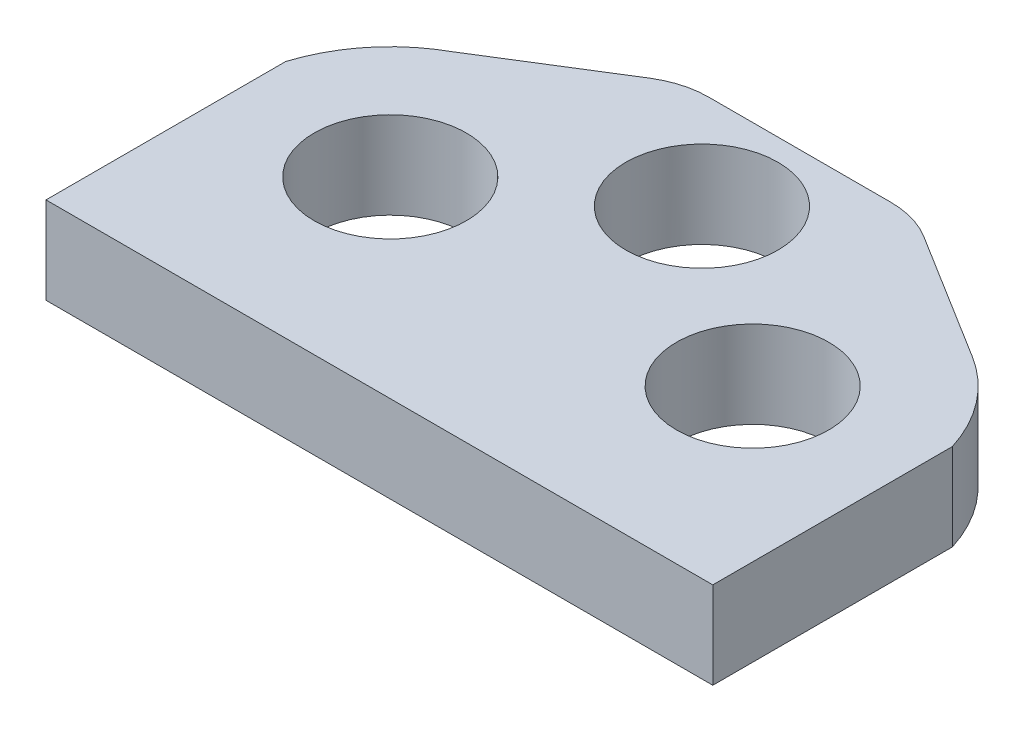
SolidWorks part; units mm, degrees
material "Beech"
ref_plane "Front Plane" through (0, 0, 0) normal (0, 0, 1) x (1, 0, 0)
ref_plane "Top Plane" through (0, 0, 0) normal (0, 1, 0) x (1, 0, 0)
ref_plane "Right Plane" through (0, 0, 0) normal (1, 0, 0) x (0, 0, -1)
sketch "Sketch1" plane through (0, 0, 0) normal (0, 1, 0) x (1, 0, 0)
  line L1 (-46, 28) -> (46, 28)
  line L2 (-46, 28) -> (-46, -28)
  line L3 (-46, -28) -> (46, -28)
  line L4 (46, 28) -> (46, -28)
  line L5 (-46, 28) -> (46, -28) construction
  line L6 (-46, -28) -> (46, 28) construction
  point P0 (0, 0)
  dimension "D1" = 56
  dimension "D2" = 92
extrude "Boss-Extrude1" add sketch "Sketch1" along normal blind 12
sketch "Sketch8" plane through (0, 12, 0) normal (0, 1, 0) x (1, 0, 0)
  line L1 (-46, 28) -> (46, 28)
  line L2 (-46, 28) -> (-46, 30)
  line L3 (-46, 30) -> (46, 30)
  line L4 (46, 28) -> (46, 30)
  dimension "D1" = 2
extrude "Boss-Extrude3" add sketch "Sketch8" against normal blind 12
sketch "Sketch2" plane through (0, 12, 0) normal (0, 1, 0) x (1, 0, 0)
  line L0 (-55.7629, -1.5) -> (57.1831, -1.5) construction
  line L1 (-46, -28) -> (46, -28) construction
  circle A0 centre (-25, -1.5) radius 10.5
  circle A1 centre (25, -1.5) radius 10.5
  point P6 (0, -28)
  dimension "D1" = 21
  dimension "D2" = 21
  dimension "D3" = 50
  dimension "D4" = 25
  dimension "D5" = 26.5
extrude "Cut-Extrude1" cut sketch "Sketch2" against normal up to next
sketch "Sketch10" plane through (0, 12, 0) normal (0, 1, 0) x (1, 0, 0)
  line L0 (-46, 5.0574) -> (-46, 30)
  line L1 (46, 30) -> (-46, 30) construction
  line L2 (-46, 30) -> (-16, 30)
  line L4 (-16, 30) -> (-35.6673, 17.7408)
  line L5 (46, 5.0574) -> (46, 30)
  line L6 (46, 30) -> (16, 30)
  line L8 (16, 30) -> (36.6154, 17.1838)
  arc A2 (-46, 5.0574) -> (-35.6673, 17.7408) centre (-25, -1.5) cw
  arc A3 (46, 5.0574) -> (36.6154, 17.1838) centre (25, -1.5) ccw
  dimension "D1" = 30
  dimension "D2" = 30
extrude "Cut-Extrude5" cut sketch "Sketch10" against normal up to next
fillet "Fillet2" radius 12 2 edges at (16, 6, -30) (-16, 6, -30)
sketch "Sketch12" plane through (0, 0, 0) normal (0, -1, 0) x (1, 0, 0)
  circle A2 centre (0, -16.5) radius 10.5 construction
  circle A5 centre (0, -16.5) radius 10.5
extrude "Cut-Extrude7" cut sketch "Sketch12" against normal up to next
